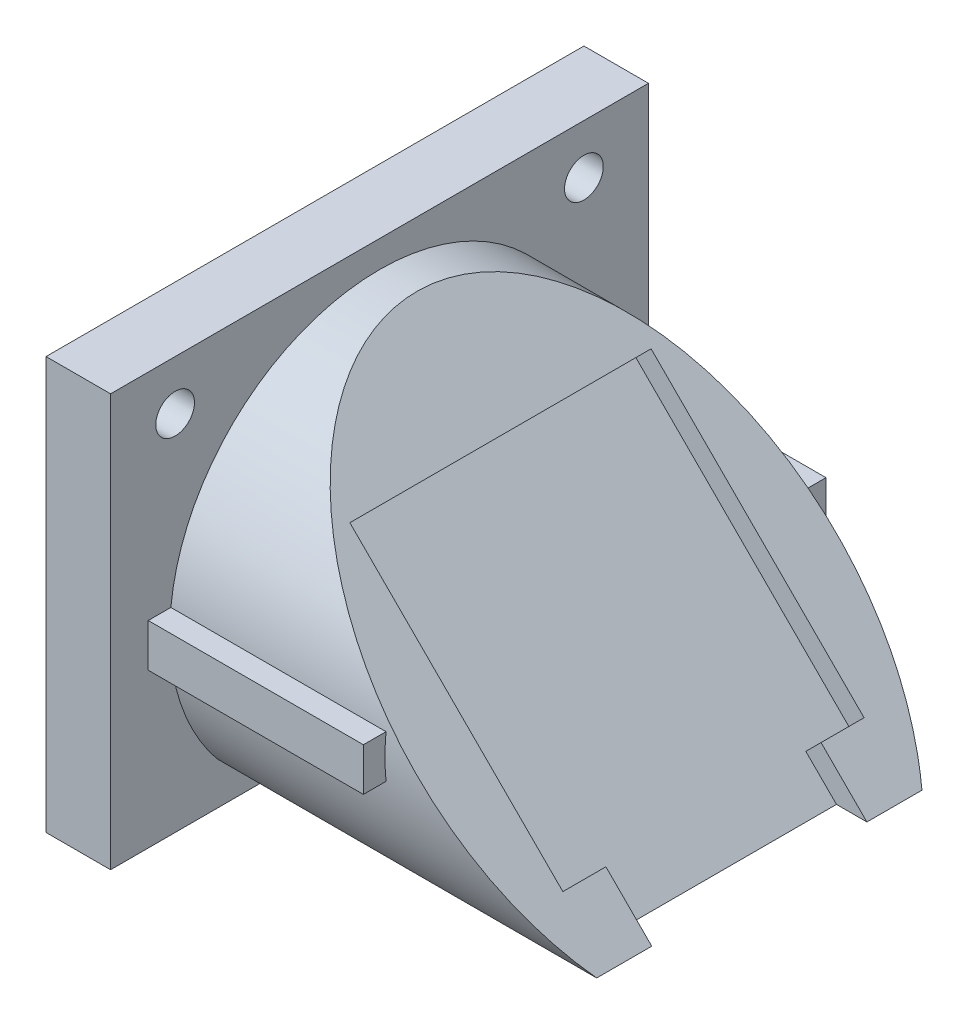
SolidWorks part; units mm, degrees
ref_plane "前视基准面" through (0, 0, 0) normal (0, 0, 1) x (1, 0, 0)
ref_plane "上视基准面" through (0, 0, 0) normal (0, 1, 0) x (1, 0, 0)
ref_plane "右视基准面" through (0, 0, 0) normal (1, 0, 0) x (0, 0, -1)
sketch "草图1" plane through (0, 0, 0) normal (1, 0, 0) x (0, 0, -1)
  line L1 (15.7093, -10) -> (-15.7093, -10)
  line L2 (15.7093, -10) -> (15.7093, 10)
  line L3 (15.7093, 10) -> (-15.7093, 10)
  line L4 (-15.7093, -10) -> (-15.7093, 10)
  line L5 (15.7093, -10) -> (-15.7093, 10) construction
  line L6 (15.7093, 10) -> (-15.7093, -10) construction
  point P0 (0, 0)
  dimension "D1" = 20
extrude "凸台-拉伸1" add sketch "草图1" along normal mid plane 40
sketch "草图2" plane through (0, 0, -15.7093) normal (0, 0, -1) x (-1, 0, 0)
  line L0 (-20, 10) -> (0, 10)
  line L1 (-20, 10) -> (20, 10) construction
  line L2 (0, 10) -> (-20, -10)
  line L3 (-20, -10) -> (-20, 10)
extrude "切除-拉伸1" cut sketch "草图2" against normal blind 40
sketch "草图3" plane through (5, 5, 0) normal (0.7071, 0.7071, 0) x (0, 0, -1)
  line L0 (-15.7093, 7.0711) -> (15.7093, 7.0711) construction
  line L1 (-7, -12.7655) -> (-5, -12.7655)
  line L2 (-7, -12.7655) -> (-7, 1.2345)
  line L3 (-7, 1.2345) -> (7, 1.2345)
  line L4 (7, -12.7655) -> (7, 1.2345)
  line L5 (-15.7093, -21.2132) -> (15.7093, -21.2132) construction
  line L7 (-5, -12.7655) -> (-5, -21.2132)
  line L8 (-5, -21.2132) -> (5, -21.2132)
  line L9 (5, -12.7655) -> (5, -21.2132)
  line L10 (0, 7.0711) -> (0, -7.2086) construction
  line L11 (5, -12.7655) -> (7, -12.7655)
  point P6 (0, 7.0711)
  point P7 (0, 1.2345)
  dimension "D1" = 10
  dimension "D2" = 14
sketch "草图5" plane through (-20, 0, 0) normal (-1, 0, 0) x (0, 0, 1)
  circle A0 centre (0, 0) radius 9.75
  dimension "D1" = 19.5
extrude "切除-拉伸2" cut sketch "草图5" against normal through all flip side to cut
extrude "切除-拉伸3" cut sketch "草图3" against normal blind 1
sketch "草图6" plane through (-20, 0, 0) normal (-1, 0, 0) x (0, 0, 1)
  circle A1 centre (0, 0) radius 9.75
  circle A2 centre (0, 0) radius 9.75
  dimension "D1" = 0
extrude "切除-拉伸4" cut sketch "草图6" against normal blind 18.5052
sketch "草图7" plane through (-1.4948, 0, 0) normal (-1, 0, 0) x (0, 0, 1)
  line L1 (12.5, -11) -> (-12.5, -11)
  line L2 (12.5, -11) -> (12.5, 11)
  line L3 (12.5, 11) -> (-12.5, 11)
  line L4 (-12.5, -11) -> (-12.5, 11)
  line L5 (12.5, -11) -> (-12.5, 11) construction
  line L6 (12.5, 11) -> (-12.5, -11) construction
  circle A3 centre (0, 0) radius 9.75 construction
  point P0 (0, 0)
  dimension "D1" = 25
  dimension "D2" = 11
extrude "凸台-拉伸2" add sketch "草图7" along normal blind 3
sketch "草图8" plane through (0, 0, 0) normal (0, 0, 1) x (1, 0, 0)
  line L1 (-8.5471, -6.1584) -> (23.1919, -6.1584)
  line L2 (-8.5471, -6.1584) -> (-8.5471, -12.8996)
  line L3 (-8.5471, -12.8996) -> (23.1919, -12.8996)
  line L4 (23.1919, -6.1584) -> (23.1919, -12.8996)
extrude "切除-拉伸5" cut sketch "草图8" against normal through all both and the other way through all
sketch "草图9" plane through (-4.4948, 0, 0) normal (-1, 0, 0) x (0, 0, 1)
  line L1 (-8.75, -1) -> (-10.75, -1)
  line L2 (-8.75, -1) -> (-8.75, 1)
  line L3 (-8.75, 1) -> (-10.75, 1)
  line L4 (-10.75, -1) -> (-10.75, 1)
  line L5 (-8.75, -1) -> (-10.75, 1) construction
  line L6 (-8.75, 1) -> (-10.75, -1) construction
  line L7 (10.75, -1) -> (8.75, -1)
  line L8 (10.75, -1) -> (10.75, 1)
  line L9 (10.75, 1) -> (8.75, 1)
  line L10 (8.75, -1) -> (8.75, 1)
  line L11 (10.75, -1) -> (8.75, 1) construction
  line L12 (10.75, 1) -> (8.75, -1) construction
  arc A0 (7.5588, -6.1584) -> (-7.5588, -6.1584) centre (0, 0) ccw construction
  point P0 (-9.75, 0)
  point P8 (9.75, 0)
  dimension "D1" = 2
extrude "凸台-拉伸3" add sketch "草图9" against normal blind 13
sketch "草图10" plane through (0, -6.1584, 0) normal (0, -1, 0) x (1, 0, 0)
  line L1 (-4.4948, 12.5) -> (-1.4948, 12.5)
  line L2 (-4.4948, 12.5) -> (-4.4948, -12.5)
  line L3 (-4.4948, -12.5) -> (-1.4948, -12.5)
  line L4 (-1.4948, 12.5) -> (-1.4948, -12.5)
extrude "凸台-拉伸4" add sketch "草图10" along normal blind 2
sketch "草图11" plane through (-4.4948, 0, 0) normal (-1, 0, 0) x (0, 0, 1)
  line L0 (-12.5, 11) -> (12.5, -8.1584) construction
  line L1 (-12.5, -8.1584) -> (12.5, 11) construction
  circle A0 centre (0, 1.4208) radius 2.3 construction
  circle A1 centre (0, 3.7208) radius 0.75
  circle A2 centre (2.3, 1.4208) radius 0.75
  circle A3 centre (0, -0.8792) radius 0.75
  circle A4 centre (-2.3, 1.4208) radius 0.75
  point P14 (0, 1.4208)
  point P20 (0, 0)
  dimension "D1" = 4.6
  dimension "D2" = 1.5
  dimension "D4" = 4.6
  dimension "D3" = 4
extrude "切除-拉伸6" cut sketch "草图11" against normal blind 4
sketch "草图13" plane through (-4.4948, 0, 0) normal (-1, 0, 0) x (0, 0, 1)
  line L0 (-12.5, 11) -> (12.5, -8.1584) construction
  line L1 (-12.5, -8.1584) -> (12.5, 11) construction
  circle A0 centre (-9.5, 8.701) radius 0.9
  circle A1 centre (9.5, 8.701) radius 0.9
  point P12 (0, 0)
  dimension "D2" = 1.8
  dimension "D1" = 19
extrude "切除-拉伸7" cut sketch "草图13" against normal through all
